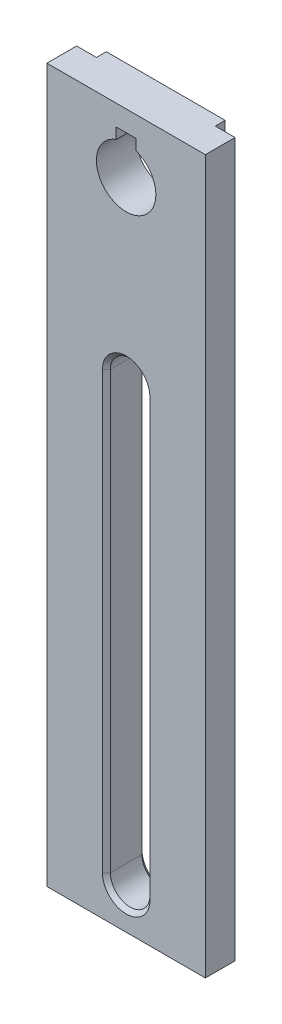
SolidWorks part; units mm, degrees
material "3.1325 (EN-AW 2017A)"
ref_plane "Płaszczyzna przednia" through (0, 0, 0) normal (0, 0, 1) x (1, 0, 0)
ref_plane "Płaszczyzna górna" through (0, 0, 0) normal (0, 1, 0) x (1, 0, 0)
ref_plane "Płaszczyzna prawa" through (0, 0, 0) normal (1, 0, 0) x (0, 0, -1)
other "Środek masy(COM)"
sketch "Szkic1" plane through (0, 0, 0) normal (0, 0, 1) x (1, 0, 0)
  line L0 (0, 20) -> (0, 200) construction
  line L1 (20, 200) -> (-20, 200)
  line L2 (-20, 200) -> (-20, 20)
  line L3 (20, 200) -> (20, 20)
  line L4 (2.5, 194.8) -> (-2.5, 194.8)
  line L5 (-2.5, 194.8) -> (-2.5, 192.0711)
  line L6 (0, 140) -> (0, 30) construction
  line L7 (5, 140) -> (5, 30)
  line L8 (-5, 140) -> (-5, 30)
  line L9 (20, 20) -> (-20, 20)
  line L10 (2.5, 194.8) -> (2.5, 192.0711)
  arc A0 (-2.5, 192.0711) -> (2.5, 192.0711) centre (0, 185) ccw
  arc A1 (5, 140) -> (-5, 140) centre (0, 140) ccw
  arc A2 (-5, 30) -> (5, 30) centre (0, 30) ccw
  point P12 (0, 85)
  point P21 (0, 194.8)
  dimension "D1" = 40
  dimension "D2" = 15
  dimension "D5" = 60
  dimension "D7" = 7.5
  dimension "D3" = 10
  dimension "D4" = 110
  dimension "D6" = 180
  dimension "D8" = 2.5
  dimension "D9" = 20
  dimension "D10" = 9.8
extrude "Dodanie-wyciągnięcie1" add sketch "Szkic1" along normal blind 10
sketch "Szkic2" plane through (0, 200, 0) normal (0, 1, 0) x (1, 0, 0)
  line L0 (-20, -2.5) -> (-15, -2.5)
  line L1 (-20, -10) -> (-20, 0) construction
  line L2 (-15, -2.5) -> (-15, 0)
  line L3 (20, 0) -> (-20, 0) construction
  line L4 (0, 0) -> (0, -10) construction
  line L5 (20, -10) -> (-20, -10) construction
  line L6 (15, -2.5) -> (15, 0)
  line L7 (20, -2.5) -> (15, -2.5)
  line L8 (-20, -2.5) -> (-20, 0)
  line L9 (-20, 0) -> (-15, 0)
  line L10 (15, 0) -> (20, 0)
  line L11 (20, 0) -> (20, -2.5)
  dimension "D1" = 5
  dimension "D2" = 2.5
extrude "Wytnij-wyciągnięcie1" cut sketch "Szkic2" against normal through all
chamfer "Sfazowanie1" distance 1 angle 45 8 edges at (0, 145, 0) (-5, 85, 0) (5, 85, 0) (0, 25, 0) (0, 145, 10) (5, 85, 10) (0, 25, 10) (-5, 85, 10)
